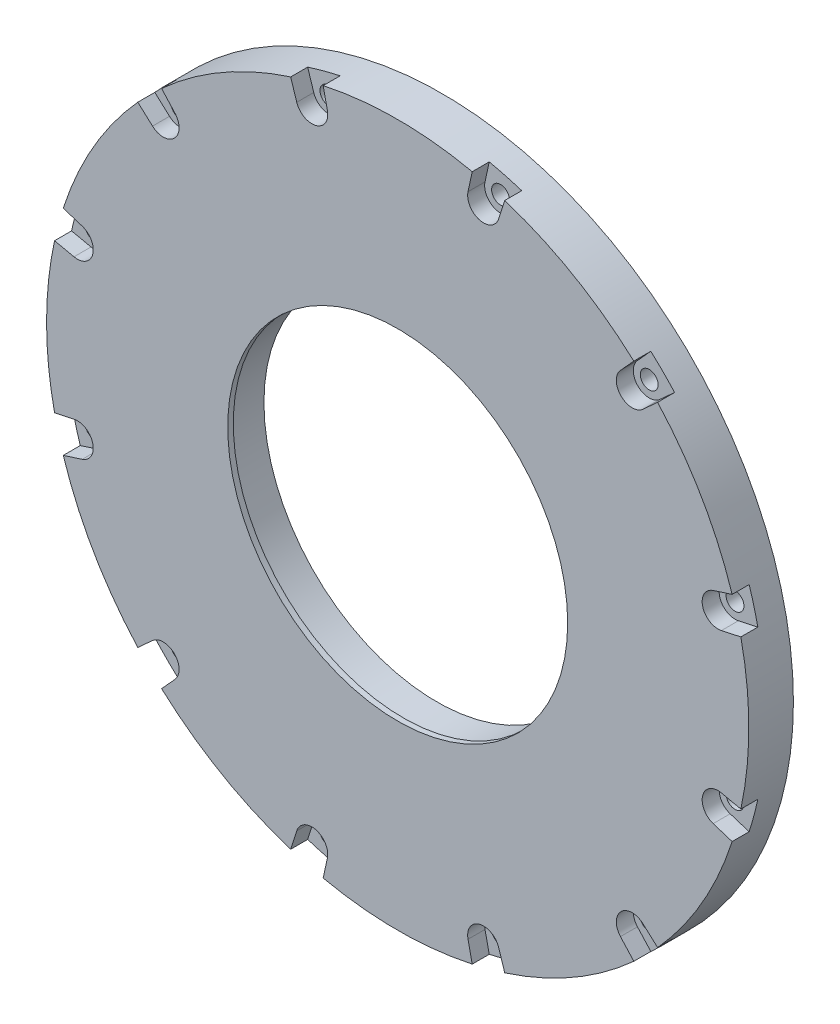
SolidWorks part; units mm, degrees
material "ABS"
ref_plane "Front Plane" through (0, 0, 0) normal (0, 0, 1) x (1, 0, 0)
ref_plane "Top Plane" through (0, 0, 0) normal (0, 1, 0) x (1, 0, 0)
ref_plane "Right Plane" through (0, 0, 0) normal (1, 0, 0) x (0, 0, -1)
sketch "CYC Master Sketch" plane through (0, 0, 19) normal (0, 0, 1) x (1, 0, 0)
  circle A0 centre (0, 0) radius 39.15
  circle A2 centre (0, 0) radius 33.5 construction
  circle A3 centre (-33.5, 0) radius 1.575
  circle A4 centre (-32.3585, 8.6704) radius 1.575
  circle A5 centre (-29.0119, 16.75) radius 1.575
  circle A6 centre (-23.6881, 23.6881) radius 1.575
  circle A7 centre (-16.75, 29.0119) radius 1.575
  circle A8 centre (-8.6704, 32.3585) radius 1.575
  circle A9 centre (0, 33.5) radius 1.575
  circle A10 centre (8.6704, 32.3585) radius 1.575
  circle A11 centre (16.75, 29.0119) radius 1.575
  circle A12 centre (23.6881, 23.6881) radius 1.575
  circle A13 centre (29.0119, 16.75) radius 1.575
  circle A14 centre (32.3585, 8.6704) radius 1.575
  circle A15 centre (33.5, 0) radius 1.575
  circle A16 centre (32.3585, -8.6704) radius 1.575
  circle A17 centre (29.0119, -16.75) radius 1.575
  circle A18 centre (23.6881, -23.6881) radius 1.575
  circle A19 centre (16.75, -29.0119) radius 1.575
  circle A20 centre (8.6704, -32.3585) radius 1.575
  circle A21 centre (0, -33.5) radius 1.575
  circle A22 centre (-8.6704, -32.3585) radius 1.575
  circle A23 centre (0, 0) radius 34
  circle A24 centre (-16.75, -29.0119) radius 1.575
  circle A25 centre (-23.6881, -23.6881) radius 1.575
  circle A26 centre (-29.0119, -16.75) radius 1.575
  circle A27 centre (-32.3585, -8.6704) radius 1.575
  circle A28 centre (0, 0) radius 31 construction
  circle A29 centre (0, 0) radius 24.975 construction
  circle A30 centre (0, 0) radius 35.75 construction
  circle A31 centre (4.6663, -35.4442) radius 1.6
  circle A32 centre (-4.6663, -35.4442) radius 1.6
  circle A33 centre (-28.3624, -21.7632) radius 1.6
  circle A34 centre (-33.0287, -13.6809) radius 1.6
  circle A35 centre (-33.0287, 13.6809) radius 1.6
  circle A36 centre (-28.3624, 21.7632) radius 1.6
  circle A37 centre (-4.6663, 35.4442) radius 1.6
  circle A38 centre (4.6663, 35.4442) radius 1.6
  circle A39 centre (28.3624, 21.7632) radius 1.6
  circle A40 centre (33.0287, 13.6809) radius 1.6
  circle A41 centre (33.0287, -13.6809) radius 1.6
  circle A42 centre (28.3624, -21.7632) radius 1.6
  point P47 (0, 0)
  point P72 (0, 0)
extrude "Boss-Extrude1" add sketch "CYC Master Sketch" along normal blind 8 contours A0 A36 A35 A34 A33 A32 A31 A27 A23 A3 A4 A5 A6 A7 A8 A9 A10 A11 A12 A13 A14 A15 A16 A17 A18 A19 A20 | A27 A23 A26 A25 A24 A22 A21 A20 A19 A18 A17 A16 A15 A14 A13 A12 A11 A10 A9 A8 A7 A6 A5 A4 A3
sketch "Sketch3" plane through (0, 0, 19) normal (0, 0, -1) x (-1, 0, 0)
  circle A1 centre (-33.5, 0) radius 1.575
  circle A2 centre (-33.5, 0) radius 1.575 construction
  circle A3 centre (-32.3585, 8.6704) radius 1.575
  circle A4 centre (-29.0119, 16.75) radius 1.575
  circle A5 centre (-23.6881, 23.6881) radius 1.575
  circle A6 centre (-16.75, 29.0119) radius 1.575
  circle A7 centre (-8.6704, 32.3585) radius 1.575
  circle A8 centre (0, 33.5) radius 1.575
  circle A9 centre (8.6704, 32.3585) radius 1.575
  circle A10 centre (16.75, 29.0119) radius 1.575
  circle A11 centre (23.6881, 23.6881) radius 1.575
  circle A12 centre (29.0119, 16.75) radius 1.575
  circle A13 centre (32.3585, 8.6704) radius 1.575
  circle A14 centre (33.5, 0) radius 1.575
  circle A15 centre (32.3585, -8.6704) radius 1.575
  circle A16 centre (29.0119, -16.75) radius 1.575
  circle A17 centre (23.6881, -23.6881) radius 1.575
  circle A18 centre (16.75, -29.0119) radius 1.575
  circle A19 centre (8.6704, -32.3585) radius 1.575
  circle A20 centre (0, -33.5) radius 1.575
  circle A21 centre (-8.6704, -32.3585) radius 1.575
  circle A22 centre (-16.75, -29.0119) radius 1.575
  circle A23 centre (-23.6881, -23.6881) radius 1.575
  circle A24 centre (-29.0119, -16.75) radius 1.575
  circle A25 centre (-32.3585, -8.6704) radius 1.575
  point P54 (0, 0)
  dimension "D1" = 24
extrude "Pin Cutout" cut sketch "Sketch3" against normal blind 4
sketch "Sketch5" plane through (0, 0, 19) normal (0, 0, -1) x (-1, 0, 0)
  circle A0 centre (0, 0) radius 31
  circle A1 centre (0, 0) radius 31 construction
extrude "Cut-Extrude2" cut sketch "Sketch5" against normal through all
sketch "Sketch6" plane through (0, 0, 27) normal (0, 0, 1) x (1, 0, 0)
  circle A0 centre (0, 0) radius 31
  circle A1 centre (0, 0) radius 31 construction
  circle A2 centre (0, 0) radius 30.5
  dimension "D1" = 0.5
extrude "Boss-Extrude2" add sketch "Sketch6" against normal blind 1
sketch "Sketch7" plane through (0, 0, 19) normal (0, 0, -1) x (-1, 0, 0)
  circle A0 centre (0, 0) radius 39.15
  circle A1 centre (0, 0) radius 39.15 construction
  circle A2 centre (0, 0) radius 63
  dimension "D1" = 126
extrude "Boss-Extrude3" add sketch "Sketch7" against normal up to surface (8 mm away) up to face at (39.15, 0, 27)
sketch "Sketch8" plane through (0, 0, 19) normal (0, 0, -1) x (-1, 0, 0)
  circle A0 centre (0, 0) radius 36.5
  dimension "D1" = 73
extrude "Cut-Extrude3" cut sketch "Sketch8" against normal blind 1
sketch "Sketch9" plane through (0, 0, 27) normal (0, 0, 1) x (1, 0, 0)
  circle A0 centre (-33.0287, -13.6809) radius 2.1
  circle A1 centre (-28.3624, -21.7632) radius 2.1
  circle A2 centre (-28.3624, 21.7632) radius 2.1
  circle A3 centre (-33.0287, 13.6809) radius 2.1
  circle A4 centre (4.6663, 35.4442) radius 2.1
  circle A5 centre (-4.6663, 35.4442) radius 2.1
  circle A6 centre (33.0287, 13.6809) radius 2.1
  circle A7 centre (28.3624, 21.7632) radius 2.1
  circle A8 centre (28.3624, -21.7632) radius 2.1
  circle A9 centre (33.0287, -13.6809) radius 2.1
  circle A10 centre (-4.6663, -35.4442) radius 2.1
  circle A11 centre (4.6663, -35.4442) radius 2.1
  point P16 (0, 0)
  dimension "D1" = 6
  dimension "M3 Insert" = 4.2
extrude "M3 L5.7 Insert Cutout" cut sketch "Sketch9" along normal blind 6 from surface at -8 starting at face at (-36.5, 0, 19)
sketch "Sketch10" plane through (0, 0, 27) normal (0, 0, 1) x (1, 0, 0)
  circle A0 centre (0, 0) radius 50 construction
  circle A1 centre (-50, 0) radius 2.1
  circle A2 centre (-43.3013, 25) radius 2.1
  circle A3 centre (-25, 43.3013) radius 2.1
  circle A4 centre (0, 50) radius 2.1
  circle A5 centre (25, 43.3013) radius 2.1
  circle A6 centre (43.3013, 25) radius 2.1
  circle A7 centre (50, 0) radius 2.1
  circle A8 centre (43.3013, -25) radius 2.1
  circle A9 centre (25, -43.3013) radius 2.1
  circle A11 centre (-25, -43.3013) radius 2.1
  circle A12 centre (-43.3013, -25) radius 2.1
  circle A13 centre (0, -50) radius 2.1 [skipped]
  point P30 (0, 0)
  dimension "D1" = 100
  dimension "D2" = 4.2
  dimension "D3" = 12
sketch "Sketch19" plane through (0, 0, 27) normal (0, 0, 1) x (1, 0, 0)
  line L0 (0, 0) -> (60.8533, 16.3056) construction
  line L1 (0, 0) -> (63, 0) construction
  circle A0 centre (0, 0) radius 63 construction
  circle A1 centre (57.4726, 15.3997) radius 3.5 construction
  circle A2 centre (57.4726, 15.3997) radius 1.6
  circle A3 centre (57.4726, -15.3997) radius 1.6
  circle A4 centre (42.0729, -42.0729) radius 1.6
  circle A5 centre (15.3997, -57.4726) radius 1.6
  circle A6 centre (-15.3997, -57.4726) radius 1.6
  circle A7 centre (-42.0729, -42.0729) radius 1.6
  circle A8 centre (-57.4726, -15.3997) radius 1.6
  circle A9 centre (-57.4726, 15.3997) radius 1.6
  circle A10 centre (-42.0729, 42.0729) radius 1.6
  circle A11 centre (-15.3997, 57.4726) radius 1.6
  circle A12 centre (15.3997, 57.4726) radius 1.6
  circle A13 centre (42.0729, 42.0729) radius 1.6
  point P34 (0, 0)
  dimension "D2" = 7
  dimension "D3" = 3.2
  dimension "D1" = 15
  dimension "D4" = 12
extrude "M3 Thru" cut sketch "Sketch19" against normal through all
sketch "Sketch20" plane through (0, 0, 27) normal (0, 0, 1) x (1, 0, 0)
  line L0 (0, 0) -> (58.0775, 12.6147) construction
  line L1 (0, 0) -> (56.6039, 18.1141) construction
  line L2 (56.6039, 18.1141) -> (60.0025, 19.2017)
  line L3 (58.0775, 12.6147) -> (61.5645, 13.3721)
  line L4 (58.0775, -12.6147) -> (61.5645, -13.3721)
  line L5 (56.6039, -18.1141) -> (60.0025, -19.2017)
  line L6 (43.9893, -39.9634) -> (46.6304, -42.3628)
  line L7 (39.9634, -43.9893) -> (42.3628, -46.6304)
  line L8 (18.1141, -56.6039) -> (19.2017, -60.0025)
  line L9 (12.6147, -58.0775) -> (13.3721, -61.5645)
  line L10 (-12.6147, -58.0775) -> (-13.3721, -61.5645)
  line L11 (-18.1141, -56.6039) -> (-19.2017, -60.0025)
  line L12 (-39.9634, -43.9893) -> (-42.3628, -46.6304)
  line L13 (-43.9893, -39.9634) -> (-46.6304, -42.3628)
  line L14 (-56.6039, -18.1141) -> (-60.0025, -19.2017)
  line L15 (-58.0775, -12.6147) -> (-61.5645, -13.3721)
  line L16 (-58.0775, 12.6147) -> (-61.5645, 13.3721)
  line L17 (-56.6039, 18.1141) -> (-60.0025, 19.2017)
  line L18 (-43.9893, 39.9634) -> (-46.6304, 42.3628)
  line L19 (-39.9634, 43.9893) -> (-42.3628, 46.6304)
  line L20 (-18.1141, 56.6039) -> (-19.2017, 60.0025)
  line L21 (-12.6147, 58.0775) -> (-13.3721, 61.5645)
  line L22 (12.6147, 58.0775) -> (13.3721, 61.5645)
  line L23 (18.1141, 56.6039) -> (19.2017, 60.0025)
  line L24 (39.9634, 43.9893) -> (42.3628, 46.6304)
  line L25 (43.9893, 39.9634) -> (46.6304, 42.3628)
  arc A0 (56.6039, 18.1141) -> (58.0775, 12.6147) centre (57.4726, 15.3997) ccw
  circle A1 centre (57.4726, 15.3997) radius 1.6 construction
  circle A2 centre (0, 0) radius 63 construction
  arc A3 (61.5645, 13.3721) -> (60.0025, 19.2017) centre (0, 0) ccw
  arc A4 (60.0025, -19.2017) -> (61.5645, -13.3721) centre (0, 0) ccw
  arc A5 (58.0775, -12.6147) -> (56.6039, -18.1141) centre (57.4726, -15.3997) ccw
  arc A6 (42.3628, -46.6304) -> (46.6304, -42.3628) centre (0, 0) ccw
  arc A7 (43.9893, -39.9634) -> (39.9634, -43.9893) centre (42.0729, -42.0729) ccw
  arc A8 (13.3721, -61.5645) -> (19.2017, -60.0025) centre (0, 0) ccw
  arc A9 (18.1141, -56.6039) -> (12.6147, -58.0775) centre (15.3997, -57.4726) ccw
  arc A10 (-19.2017, -60.0025) -> (-13.3721, -61.5645) centre (0, 0) ccw
  arc A11 (-12.6147, -58.0775) -> (-18.1141, -56.6039) centre (-15.3997, -57.4726) ccw
  arc A12 (-46.6304, -42.3628) -> (-42.3628, -46.6304) centre (0, 0) ccw
  arc A13 (-39.9634, -43.9893) -> (-43.9893, -39.9634) centre (-42.0729, -42.0729) ccw
  arc A14 (-61.5645, -13.3721) -> (-60.0025, -19.2017) centre (0, 0) ccw
  arc A15 (-56.6039, -18.1141) -> (-58.0775, -12.6147) centre (-57.4726, -15.3997) ccw
  arc A16 (-60.0025, 19.2017) -> (-61.5645, 13.3721) centre (0, 0) ccw
  arc A17 (-58.0775, 12.6147) -> (-56.6039, 18.1141) centre (-57.4726, 15.3997) ccw
  arc A18 (-42.3628, 46.6304) -> (-46.6304, 42.3628) centre (0, 0) ccw
  arc A19 (-43.9893, 39.9634) -> (-39.9634, 43.9893) centre (-42.0729, 42.0729) ccw
  arc A20 (-13.3721, 61.5645) -> (-19.2017, 60.0025) centre (0, 0) ccw
  arc A21 (-18.1141, 56.6039) -> (-12.6147, 58.0775) centre (-15.3997, 57.4726) ccw
  arc A22 (19.2017, 60.0025) -> (13.3721, 61.5645) centre (0, 0) ccw
  arc A23 (12.6147, 58.0775) -> (18.1141, 56.6039) centre (15.3997, 57.4726) ccw
  arc A24 (46.6304, 42.3628) -> (42.3628, 46.6304) centre (0, 0) ccw
  arc A25 (39.9634, 43.9893) -> (43.9893, 39.9634) centre (42.0729, 42.0729) ccw
  point P68 (0, 0)
  dimension "D1" = 5.7
  dimension "D2" = 12
extrude "M3 Socket Head Cap Cut" cut sketch "Sketch20" against normal blind 3.05
fillet "Fillet1" [suppressed] radius 0.5
sketch "Sketch21" plane through (0, 0, 27) normal (0, 0, 1) x (1, 0, 0)
  line L0 (0, 0) -> (0, -63) construction
  line L1 (-8.7021, -42.1577) -> (-9.3278, -46.1085)
  line L2 (8.7021, -42.1577) -> (9.3278, -46.1085)
  arc A1 (7.6653, -48.3967) -> (-7.6653, -48.3967) centre (0, 0) cw
  arc A2 (6.4138, -40.4952) -> (-6.4138, -40.4952) centre (0, 0) cw
  arc A3 (-7.6653, -48.3967) -> (-9.3278, -46.1085) centre (-7.3524, -46.4214) cw
  arc A4 (-8.7021, -42.1577) -> (-6.4138, -40.4952) centre (-6.7267, -42.4706) cw
  arc A5 (7.6653, -48.3967) -> (9.3278, -46.1085) centre (7.3524, -46.4214) ccw
  arc A6 (8.7021, -42.1577) -> (6.4138, -40.4952) centre (6.7267, -42.4706) ccw
  point P4 (-9.6343, -48.0435)
  point P13 (-8.3816, -40.1341)
  dimension "D1" = 41
  dimension "D2" = 49
  dimension "D5" = 2
  dimension "D3" = 18
  dimension "D4" = 18
sketch "Sketch26" plane through (0, 0, 27) normal (0, 0, 1) x (1, 0, 0)
  line L0 (0, 0) -> (-9.356, 44.0166) construction
  line L1 (0, 0) -> (9.356, 44.0166) construction
  line L2 (-9.0388, 42.5241) -> (-8.4146, 39.5878)
  line L3 (9.0388, 42.5241) -> (8.4146, 39.5878)
  line L4 (0, 0) -> (0, 80.1237) construction
  arc A3 (-6.6901, 38.4219) -> (6.6901, 38.4219) centre (0, 0) cw
  arc A4 (-7.8326, 44.3131) -> (7.8326, 44.3131) centre (0, 0) cw
  arc A5 (-6.6901, 38.4219) -> (-8.4146, 39.5878) centre (-6.9474, 39.8997) cw
  arc A6 (6.6901, 38.4219) -> (8.4146, 39.5878) centre (6.9474, 39.8997) ccw
  arc A7 (7.8326, 44.3131) -> (9.0388, 42.5241) centre (7.5716, 42.836) cw
  arc A8 (-7.8326, 44.3131) -> (-9.0388, 42.5241) centre (-7.5716, 42.836) ccw
  point P16 (-8.1086, 38.1478)
  point P19 (8.1086, 38.1478)
  dimension "D2" = 39
  dimension "D1" = 45
  dimension "D5" = 1.5
  dimension "D3" = 12
  dimension "D4" = 12
equation "\"D4@Sketch21\"=\"D3@Sketch21\""
equation "\"D4@Sketch26\"=\"D3@Sketch26\""
